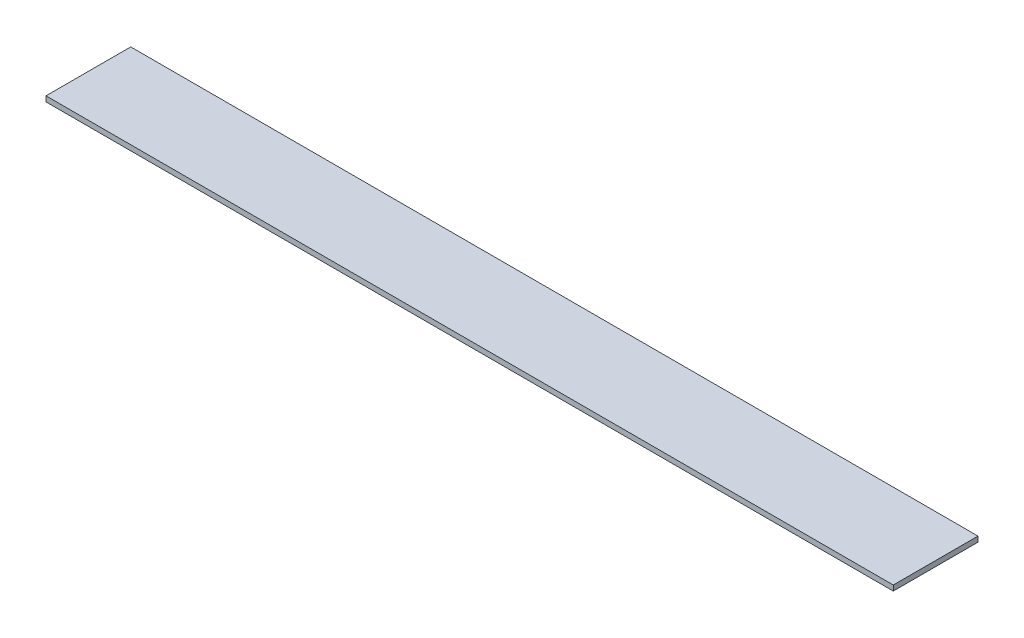
SolidWorks part; units mm, degrees
material "Nylon 101"
ref_plane "Front Plane" through (0, 0, 0) normal (0, 0, 1) x (1, 0, 0)
ref_plane "Top Plane" through (0, 0, 0) normal (0, 1, 0) x (1, 0, 0)
ref_plane "Right Plane" through (0, 0, 0) normal (1, 0, 0) x (0, 0, -1)
sketch "Sketch1" plane through (0, 0, 0) normal (0, 1, 0) x (1, 0, 0)
  line L1 (0, 0) -> (254, 0)
  line L2 (0, 0) -> (0, 25.4)
  line L3 (0, 25.4) -> (254, 25.4)
  line L4 (254, 0) -> (254, 25.4)
  dimension "D1" = 25.4
  dimension "D2" = 254
extrude "Boss-Extrude1" add sketch "Sketch1" along normal blind 1.5875
